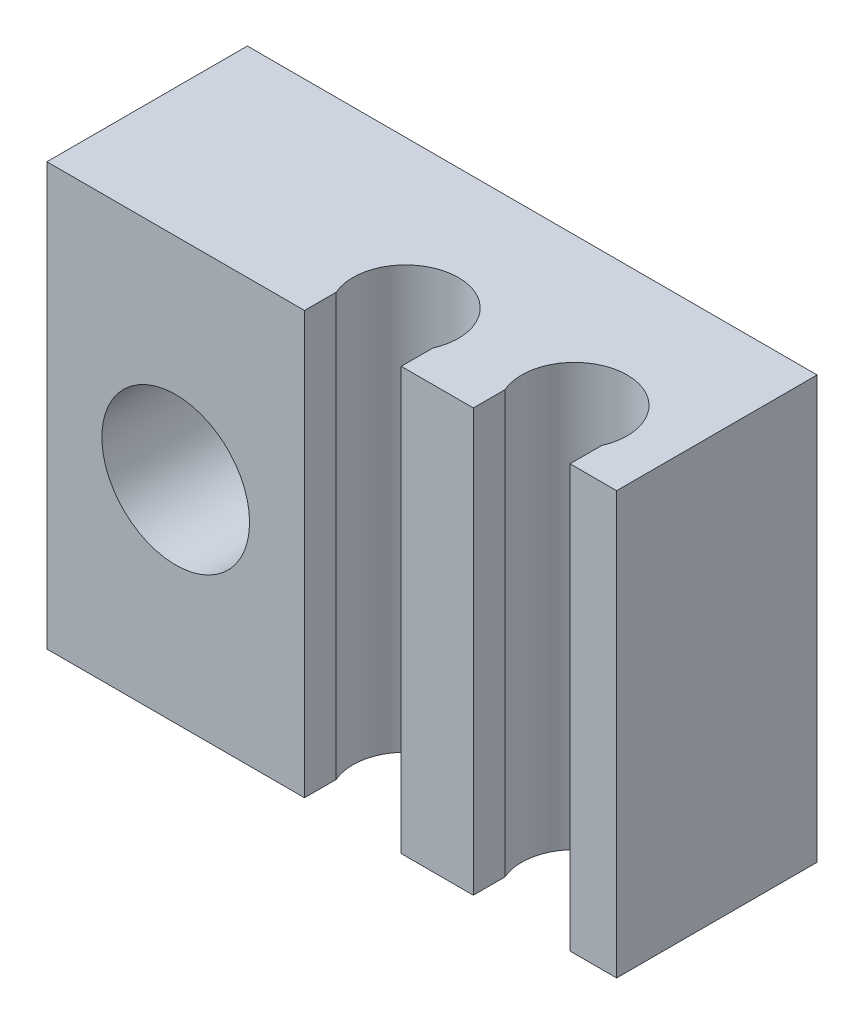
SolidWorks part; units mm, degrees
ref_plane "Front Plane" through (0, 0, 0) normal (0, 0, 1) x (1, 0, 0)
ref_plane "Top Plane" through (0, 0, 0) normal (0, 1, 0) x (1, 0, 0)
ref_plane "Right Plane" through (0, 0, 0) normal (1, 0, 0) x (0, 0, -1)
sketch "Sketch1" plane through (0, 0, 0) normal (0, 1, 0) x (1, 0, 0)
  line L0 (2.25, 0.5) -> (2.25, 0) construction
  line L1 (0, 0) -> (1.1044, 0)
  line L2 (0, 0) -> (0, 4)
  line L3 (0, 4) -> (8.5, 4)
  line L4 (8.5, 0) -> (8.5, 4)
  line L5 (1, 0.5) -> (0, 0.5) construction
  line L6 (3.5, 0.5) -> (5, 0.5) construction
  line L7 (-5, 0) -> (-5, -0.75)
  line L8 (0, 4) -> (-5, 4)
  line L9 (0, 4) -> (0, 0)
  line L10 (0, 0) -> (-5, 0)
  line L11 (-5, 4) -> (-5, 0)
  line L12 (-5, -0.75) -> (8.5, -0.75)
  line L13 (8.5, -0.75) -> (8.5, 0)
  line L14 (3.3956, 0) -> (5.1044, 0)
  line L15 (7.3956, 0) -> (8.5, 0)
  line L16 (1.1044, 0) -> (1.1044, -0.75)
  line L17 (3.3956, 0) -> (3.3956, -0.75)
  line L18 (5.1044, 0) -> (5.1044, -0.75)
  line L19 (7.3956, 0) -> (7.3956, -0.75)
  arc A0 (3.3956, 0) -> (1.1044, 0) centre (2.25, 0.5) ccw
  arc A1 (7.3956, 0) -> (5.1044, 0) centre (6.25, 0.5) ccw
  dimension "D2" = 2.5
  dimension "D7" = 1.5
  dimension "D1" = 4
  dimension "D3" = 0.5
  dimension "D4" = 1
  dimension "D5" = 8.5
  dimension "D8" = 5
  dimension "D6" = 2
extrude "Boss-Extrude1" add sketch "Sketch1" along normal blind 10 contours L8 L11 L10 L2 | A1 L1 L4 L3 L2 A0 | L16 L1 L10 L7 L12 | L18 L14 L17 L12 | L15 L19 L12 L13
sketch "Sketch4" plane through (0, 0, 0.75) normal (0, 0, 1) x (1, 0, 0)
  line L0 (-5, 10) -> (1.1044, 0) construction
  circle A0 centre (-1.9478, 5) radius 1.75
  dimension "D1" = 3.5
extrude "Cut-Extrude2" cut sketch "Sketch4" against normal through all
